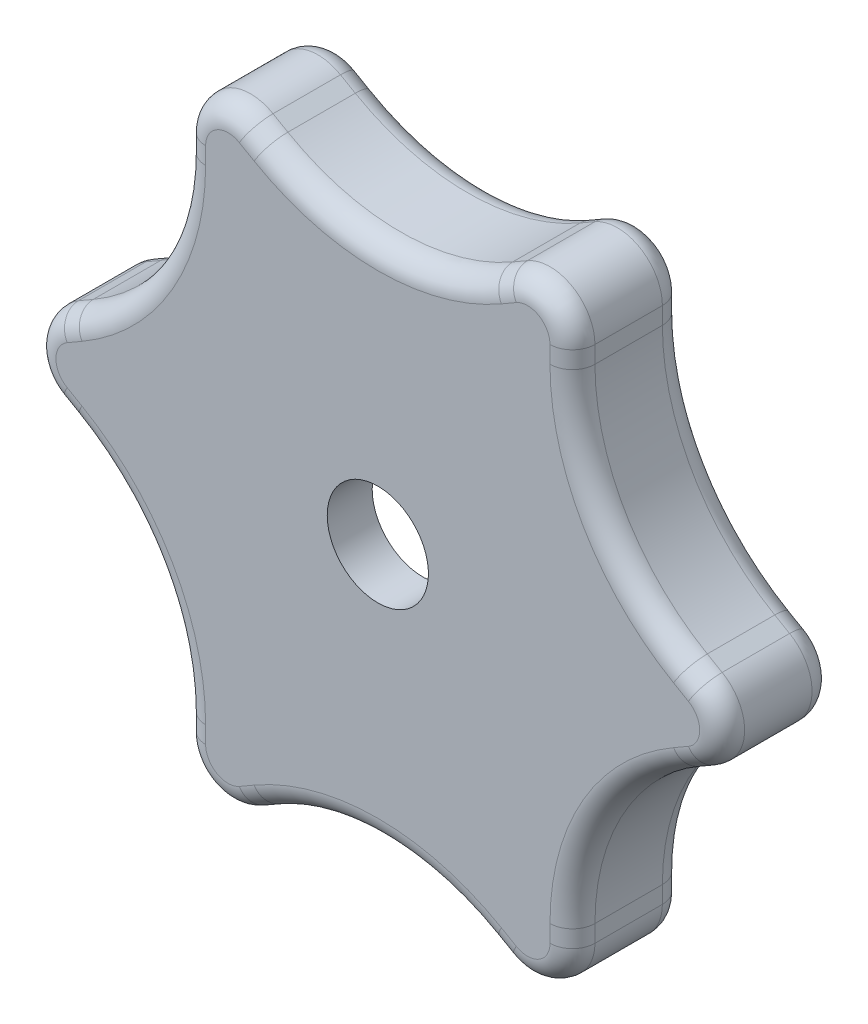
SolidWorks part; units mm, degrees
material "BUTYL"
ref_plane "前视基准面" through (0, 0, 0) normal (0, 0, 1) x (1, 0, 0)
ref_plane "上视基准面" through (0, 0, 0) normal (0, 1, 0) x (1, 0, 0)
ref_plane "右视基准面" through (0, 0, 0) normal (1, 0, 0) x (0, 0, -1)
other "Configuration Table"
sketch "草图1" plane through (0, 0, 0) normal (0, 0, 1) x (1, 0, 0)
  line L0 (-14.3205, 1.7321) -> (-13.6603, 2.1132)
  line L7 (8.6603, 11.5359) -> (8.6603, 10.7735)
  line L8 (5.6603, -13.2679) -> (5, -12.8868)
  line L9 (-8.6603, -11.5359) -> (-8.6603, -10.7735)
  line L10 (-5.6603, 13.2679) -> (-5, 12.8868)
  line L11 (14.3205, -1.7321) -> (13.6603, -2.1132)
  line L12 (5, 12.8868) -> (5.6603, 13.2679)
  line L13 (13.6603, 2.1132) -> (14.3205, 1.7321)
  line L14 (8.6603, -10.7735) -> (8.6603, -11.5359)
  line L15 (-5, -12.8868) -> (-5.6603, -13.2679)
  line L16 (-13.6603, -2.1132) -> (-14.3205, -1.7321)
  line L17 (-8.6603, 10.7735) -> (-8.6603, 11.5359)
  arc A0 (-6.2765, 13.6237) -> (-8.6603, 12.2474) centre (0, 0) ccw construction
  arc A1 (-8.6603, -12.2474) -> (-6.2765, -13.6237) centre (0, 0) ccw construction
  arc A2 (6.2765, -13.6237) -> (8.6603, -12.2474) centre (0, 0) ccw construction
  arc A3 (14.9367, -1.3763) -> (14.9367, 1.3763) centre (0, 0) ccw construction
  arc A4 (8.6603, 12.2474) -> (6.2765, 13.6237) centre (0, 0) ccw construction
  arc A5 (-13.6603, -2.1132) -> (-8.6603, -10.7735) centre (-18.6603, -10.7735) cw
  arc A6 (-5, -12.8868) -> (5, -12.8868) centre (0, -21.547) cw
  arc A7 (8.6603, -10.7735) -> (13.6603, -2.1132) centre (18.6603, -10.7735) cw
  arc A8 (13.6603, 2.1132) -> (8.6603, 10.7735) centre (18.6603, 10.7735) cw
  arc A9 (5, 12.8868) -> (-5, 12.8868) centre (0, 21.547) cw
  arc A10 (-13.6603, 2.1132) -> (-8.6603, 10.7735) centre (-18.6603, 10.7735) ccw
  arc A11 (-14.3205, 1.7321) -> (-14.3205, -1.7321) centre (-13.3205, 0) ccw
  arc A12 (-8.6603, -11.5359) -> (-5.6603, -13.2679) centre (-6.6603, -11.5359) ccw
  arc A13 (8.6603, -11.5359) -> (5.6603, -13.2679) centre (6.6603, -11.5359) cw
  arc A14 (14.3205, 1.7321) -> (14.3205, -1.7321) centre (13.3205, 0) cw
  arc A15 (8.6603, 11.5359) -> (5.6603, 13.2679) centre (6.6603, 11.5359) ccw
  arc A16 (-5.6603, 13.2679) -> (-8.6603, 11.5359) centre (-6.6603, 11.5359) ccw
  point P36 (-8.6603, 5)
  point P45 (17.3205, 0)
  dimension "D1" = 10
  dimension "D2" = 2
extrude "凸台-拉伸1" add sketch "草图1" along normal blind 5
sketch "草图2" plane through (0, 0, 0) normal (0, 0, -1) x (-1, 0, 0)
  circle A0 centre (0, 0) radius 10
  dimension "D1" = 20
extrude "切除-拉伸1" cut sketch "草图2" against normal blind 3
sketch "草图3" plane through (0, 0, 3) normal (0, 0, -1) x (-1, 0, 0)
  circle A0 centre (0, 0) radius 2.25
  dimension "D1" = 4.5
extrude "切除-拉伸2" cut sketch "草图3" against normal blind 3
fillet "圆角1" radius 1 48 edges at (13.9904, 1.9226, 5) (15.3205, 0, 5) (13.9904, -1.9226, 5) (10, -5.7735, 5) (8.6603, -11.1547, 5) (7.6603, -13.2679, 5) (5.3301, -13.0774, 5) (0, -11.547, 5) (-5.3301, -13.0774, 5) (-7.6603, -13.2679, 5) (-8.6603, -11.1547, 5) (-10, -5.7735, 5) (-13.9904, -1.9226, 5) (-15.3205, 0, 5) (-13.9904, 1.9226, 5) (-10, 5.7735, 5) (-8.6603, 11.1547, 5) (-7.6603, 13.2679, 5) (-5.3301, 13.0774, 5) (0, 11.547, 5) (5.3301, 13.0774, 5) (7.6603, 13.2679, 5) (8.6603, 11.1547, 5) (13.9904, 1.9226, 0) (15.3205, 0, 0) (13.9904, -1.9226, 0) (10, -5.7735, 0) (8.6603, -11.1547, 0) (7.6603, -13.2679, 0) (5.3301, -13.0774, 0) (0, -11.547, 0) (-5.3301, -13.0774, 0) (-7.6603, -13.2679, 0) (-8.6603, -11.1547, 0) (-10, -5.7735, 0) (-13.9904, -1.9226, 0) (-15.3205, 0, 0) (-13.9904, 1.9226, 0) (-10, 5.7735, 0) (-8.6603, 11.1547, 0) (-7.6603, 13.2679, 0) (-5.3301, 13.0774, 0) (0, 11.547, 0) (5.3301, 13.0774, 0) (7.6603, 13.2679, 0) (8.6603, 11.1547, 0) (10, 5.7735, 5) (10, 5.7735, 0)
